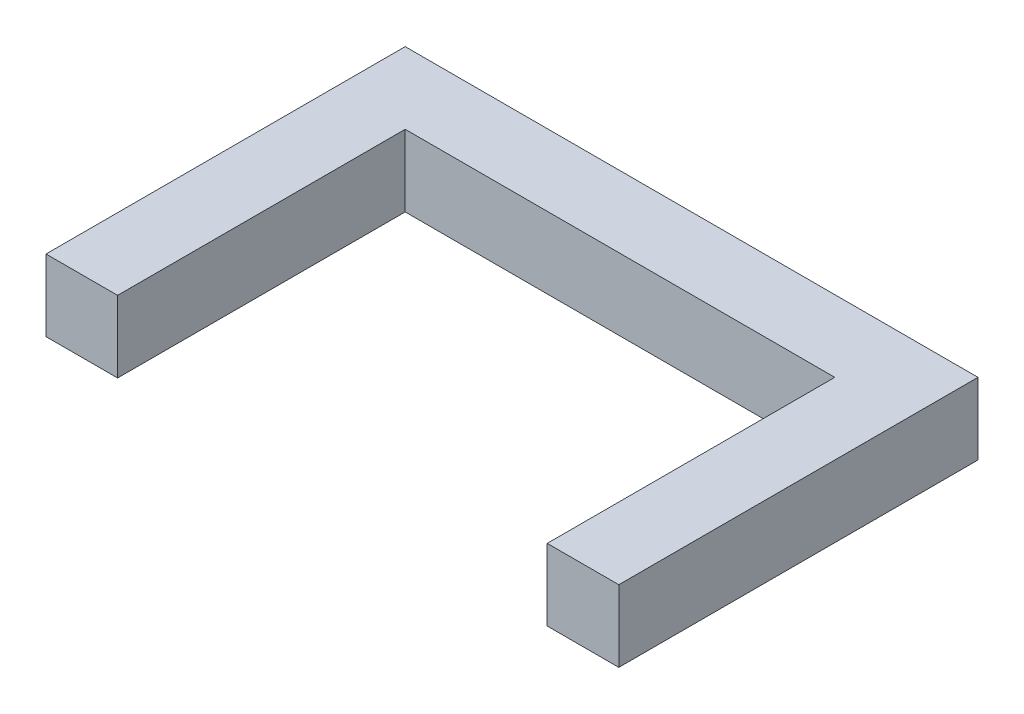
SolidWorks part; units mm, degrees
ref_plane "Front Plane" through (0, 0, 0) normal (0, 0, 1) x (1, 0, 0)
ref_plane "Top Plane" through (0, 0, 0) normal (0, 1, 0) x (1, 0, 0)
ref_plane "Right Plane" through (0, 0, 0) normal (1, 0, 0) x (0, 0, -1)
sketch "Sketch1" plane through (0, 0, 0) normal (0, 1, 0) x (1, 0, 0)
  line L0 (0, 0) -> (0, 20.066)
  line L1 (0, 20.066) -> (32, 20.066)
  line L2 (32, 20.066) -> (32, 0)
  line L3 (32, 0) -> (28, 0)
  line L4 (28, 0) -> (28, 16.066)
  line L5 (28, 16.066) -> (4, 16.066)
  line L6 (4, 16.066) -> (4, 0)
  line L7 (4, 0) -> (0, 0)
  dimension "D1" = 20.066
  dimension "D2" = 4
  dimension "D3" = 4
  dimension "D4" = 4
  dimension "D5" = 24
extrude "Boss-Extrude1" add sketch "Sketch1" along normal blind 4
